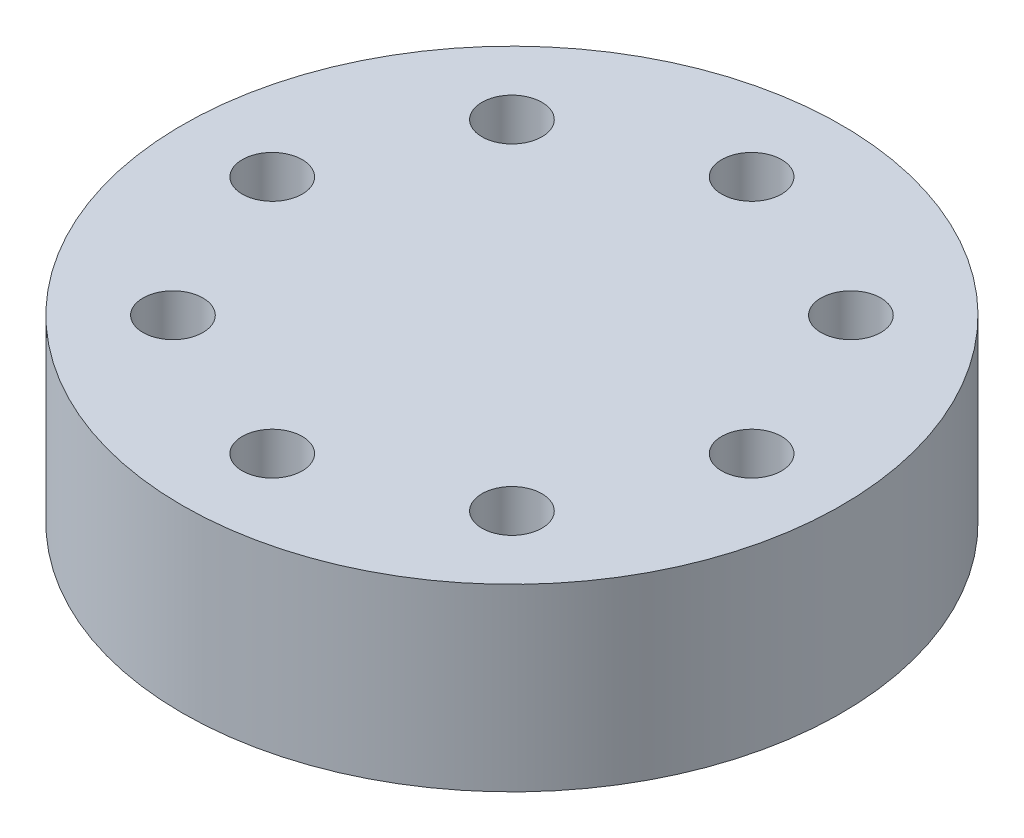
SolidWorks part; units mm, degrees
ref_plane "Front Plane" through (0, 0, 0) normal (0, 0, 1) x (1, 0, 0)
ref_plane "Top Plane" through (0, 0, 0) normal (0, 1, 0) x (1, 0, 0)
ref_plane "Right Plane" through (0, 0, 0) normal (1, 0, 0) x (0, 0, -1)
sketch "Sketch1" plane through (0, 0, 0) normal (0, 1, 0) x (1, 0, 0)
  circle A0 centre (0, 0) radius 11
  circle A1 centre (0, 0) radius 8 construction
  circle A2 centre (0, 8) radius 1
  circle A3 centre (5.6569, 5.6569) radius 1
  circle A4 centre (8, 0) radius 1
  circle A5 centre (5.6569, -5.6569) radius 1
  circle A6 centre (0, -8) radius 1
  circle A7 centre (-5.6569, -5.6569) radius 1
  circle A8 centre (-8, 0) radius 1
  circle A9 centre (-5.6569, 5.6569) radius 1
  point P22 (0, 0)
  dimension "D1" = 22
  dimension "D2" = 16
  dimension "D3" = 2
  dimension "D4" = 8
extrude "Boss-Extrude1" add sketch "Sketch1" along normal blind 6
sketch "Sketch2" plane through (0, 0, 0) normal (0, -1, 0) x (1, 0, 0)
  circle A0 centre (0, 0) radius 4
  dimension "D1" = 8
extrude "Cut-Extrude1" cut sketch "Sketch2" against normal blind 5.5
